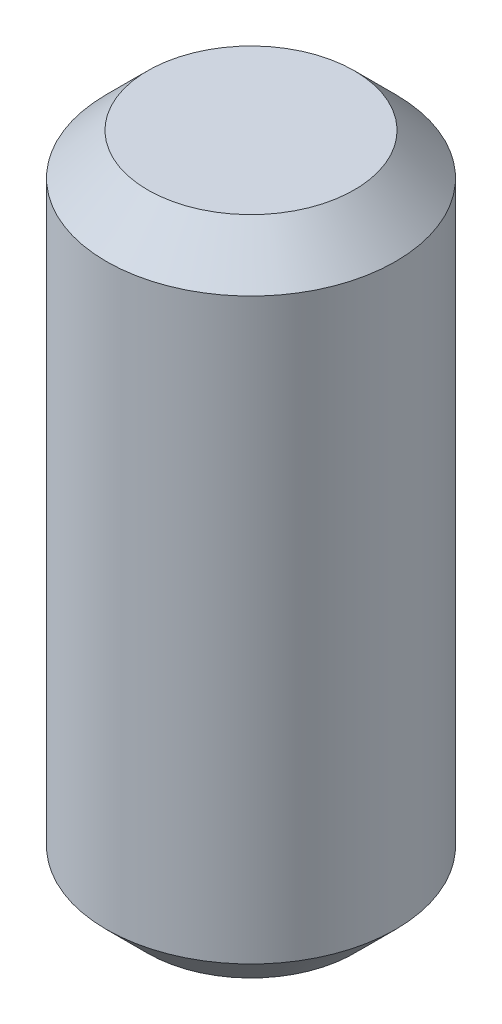
SolidWorks part; units mm, degrees
ref_plane "Front Plane" through (0, 0, 0) normal (0, 0, 1) x (1, 0, 0)
ref_plane "Top Plane" through (0, 0, 0) normal (0, 1, 0) x (1, 0, 0)
ref_plane "Right Plane" through (0, 0, 0) normal (1, 0, 0) x (0, 0, -1)
sketch "Sketch1" plane through (0, 0, 0) normal (0, 1, 0) x (1, 0, 0)
  circle A0 centre (0, 0) radius 1.75
  dimension "D1" = 3.5
extrude "Boss-Extrude1" add sketch "Sketch1" against normal blind 8
chamfer "Chamfer1" distance 0.5 angle 45 2 edges at (0, -8, 1.75) (0, 0, 1.75)
